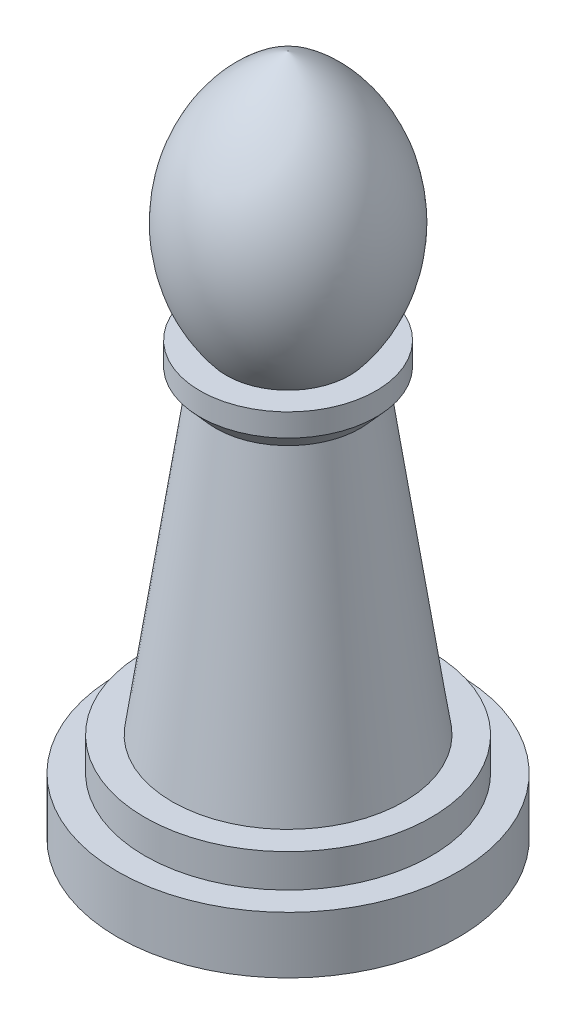
SolidWorks part; units mm, degrees
ref_plane "Front Plane" through (0, 0, 0) normal (0, 0, 1) x (1, 0, 0)
ref_plane "Top Plane" through (0, 0, 0) normal (0, 1, 0) x (1, 0, 0)
ref_plane "Right Plane" through (0, 0, 0) normal (1, 0, 0) x (0, 0, -1)
sketch "Sketch1" plane through (0, 0, 0) normal (0, 0, 1) x (1, 0, 0)
  line L0 (0, 38.1) -> (0, 0) construction
  line L1 (0, 0) -> (0, 38.1)
  line L2 (0, 0) -> (-9.525, 0)
  line L4 (-8.001, 3.175) -> (-9.525, 3.175)
  line L5 (-9.525, 0) -> (-9.525, 3.175)
  line L8 (-6.477, 5.0337) -> (-8.001, 5.0337)
  line L9 (-8.001, 3.175) -> (-8.001, 5.0337)
  line L11 (-6.477, 5.0337) -> (-4.0386, 21.8739)
  line L13 (-4.0386, 21.8739) -> (-4.9191, 22.86)
  line L16 (-4.9191, 22.86) -> (-4.9191, 24.13)
  line L17 (-4.9191, 24.13) -> (-3.4376, 24.13)
  arc A0 (-3.4376, 24.13) -> (0, 38.1) centre (3.495, 29.832) cw
  point P17 (-3.1496, 23.0632)
  dimension "D1" = 3.175
  dimension "D2" = 9.525
  dimension "D3" = 1.524
  dimension "D4" = 1.524
  dimension "D5" = 22.86
  dimension "D8" = 38.1
  dimension "D6" = 1.27
  dimension "D7" = 230
revolve "Revolve1" add sketch "Sketch1" angle 360 about L0
